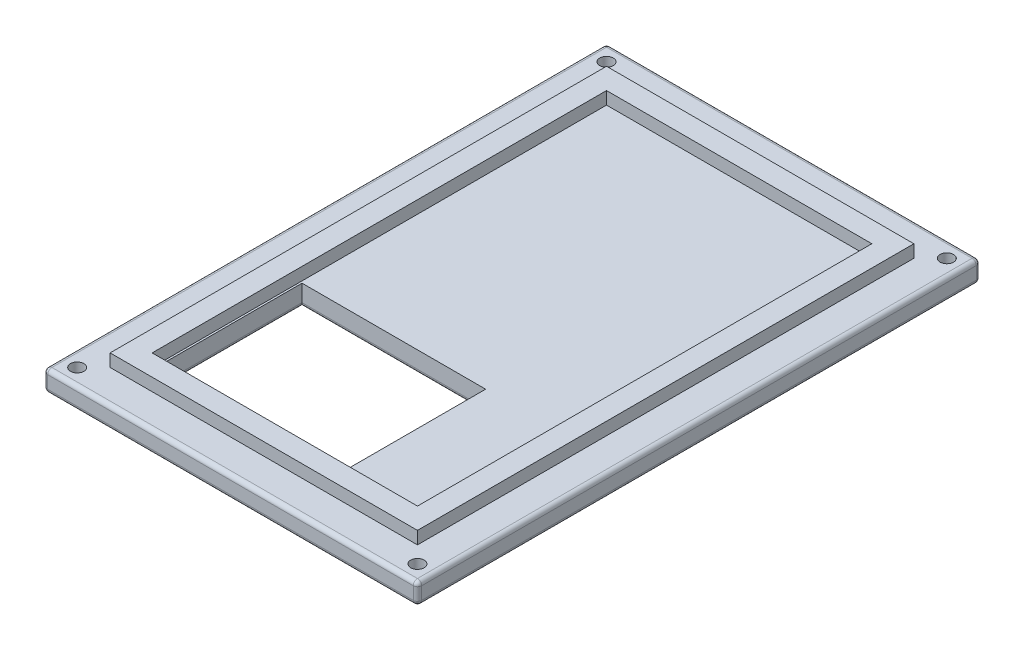
SolidWorks part; units mm, degrees
ref_plane "前基準面" through (0, 0, 0) normal (0, 0, 1) x (1, 0, 0)
ref_plane "上基準面" through (0, 0, 0) normal (0, 1, 0) x (1, 0, 0)
ref_plane "右基準面" through (0, 0, 0) normal (1, 0, 0) x (0, 0, -1)
sketch "Sketch1" plane through (0, 0, 0) normal (0, 1, 0) x (1, 0, 0)
  line L1 (-44.5, -67) -> (44.5, -67)
  line L2 (-44.5, -67) -> (-44.5, 67)
  line L3 (-44.5, 67) -> (44.5, 67)
  line L4 (44.5, -67) -> (44.5, 67)
  line L5 (-44.5, -67) -> (44.5, 67) construction
  line L6 (-44.5, 67) -> (44.5, -67) construction
  point P0 (0, 0)
  dimension "D1" = 89
  dimension "D2" = 134
extrude "Boss-Extrude1" add sketch "Sketch1" along normal mid plane 5
sketch "Sketch3" plane through (0, 2.5, 0) normal (0, 1, 0) x (1, 0, 0)
  line L0 (-31.575, -54.075) -> (-31.575, 54.075)
  line L1 (-36.575, -59.075) -> (36.575, -59.075)
  line L2 (-36.575, -59.075) -> (-36.575, 59.075)
  line L3 (-36.575, 59.075) -> (36.575, 59.075)
  line L4 (36.575, -59.075) -> (36.575, 59.075)
  line L5 (-36.575, -59.075) -> (36.575, 59.075) construction
  line L6 (-36.575, 59.075) -> (36.575, -59.075) construction
  line L7 (-31.575, 54.075) -> (31.575, 54.075)
  line L8 (31.575, -54.075) -> (31.575, 54.075)
  line L9 (-31.575, -54.075) -> (31.575, -54.075)
  point P0 (0, 0)
  dimension "D1" = 73.15
  dimension "D2" = 118.15
  dimension "D3" = 5
extrude "Boss-Extrude2" add sketch "Sketch3" along normal blind 3
sketch "Sketch5" plane through (0, -2.5, 0) normal (0, -1, 0) x (1, 0, 0)
  line L0 (-9.2606, 49.7699) -> (-9.2606, 23.1699) construction
  line L1 (3.7694, 49.7699) -> (-22.2906, 49.7699) construction
  line L2 (-0.5306, 23.1699) -> (-19.7906, 23.1699) construction
  line L3 (-9.2606, 23.1699) -> (-9.2606, 67) construction
  line L4 (44.5, 67) -> (-44.5, 67) construction
  line L5 (3.7694, 36.4199) -> (-24.1894, 36.4199) construction
  line L6 (3.7694, 49.7699) -> (3.7694, 23.0699) construction
  line L7 (44.5, -67) -> (-44.5, 67) construction
  line L8 (-31.575, 54.075) -> (31.575, 54.075) construction
  line L9 (12.5902, 18.8648) -> (-31.1113, 18.8648)
  line L10 (12.5902, 18.8648) -> (12.5902, 54.075)
  line L11 (12.5902, 54.075) -> (-31.1113, 54.075)
  line L12 (-31.1113, 18.8648) -> (-31.1113, 54.075)
  line L13 (12.5902, 18.8648) -> (-31.1113, 54.075) construction
  line L14 (12.5902, 54.075) -> (-31.1113, 18.8648) construction
  line L15 (-44.5, -67) -> (-44.5, 67) construction
  point P15 (-9.2606, 36.4699)
  dimension "D1" = 13.3887
extrude "Cut-Extrude1" cut sketch "Sketch5" against normal up to next
fillet "Fillet1" radius 1 16 edges at (44.5, 2.5, 0) (0, 2.5, 67) (44.5, 0, 67) (-44.5, 2.5, 0) (-44.5, 0, 67) (44.5, 0, -67) (0, 2.5, -67) (-44.5, 0, -67) (0, -2.5, -67) (-44.5, -2.5, 0) (0, -2.5, 67) (44.5, -2.5, 0) (-9.2606, -2.5, 18.8648) (12.5902, -2.5, 36.4699) (-9.2606, -2.5, 54.075) (-31.1113, -2.5, 36.4699)
sketch "Sketch8" plane through (0, -2.5, 0) normal (0, -1, 0) x (1, 0, 0)
  line L0 (43.5, -66) -> (35.4563, -57.9563) construction
  line L1 (44.5, 0) -> (-44.5, 0) construction
  line L2 (44.5, -67) -> (44.5, 67) construction
  line L3 (-44.5, -67) -> (-44.5, 67) construction
  line L4 (0, -67) -> (0, 67) construction
  line L5 (44.5, -67) -> (-44.5, -67) construction
  line L6 (44.5, 67) -> (-44.5, 67) construction
  circle A1 centre (40.4948, -62.9948) radius 2.9
  circle A2 centre (-40.4948, -62.9948) radius 2.9
  circle A3 centre (40.4948, 62.9948) radius 2.9
  circle A4 centre (-40.4948, 62.9948) radius 2.9
  dimension "D2" = 5.8
  dimension "D1" = 4.25
  dimension "D3" = 9.0437
  dimension "D4" = 9.0437
extrude "Cut-Extrude2" cut sketch "Sketch8" against normal blind 2.5
sketch "Sketch9" plane through (0, 0, 0) normal (0, -1, 0) x (1, 0, 0)
  circle A0 centre (40.4948, -62.9948) radius 1.6
  circle A1 centre (-40.4948, -62.9948) radius 1.6
  circle A2 centre (40.4948, 62.9948) radius 1.6
  circle A3 centre (-40.4948, 62.9948) radius 1.6
  dimension "D1" = 3.2
  dimension "D2" = 3.2
  dimension "D3" = 3.2
  dimension "D4" = 3.2
extrude "Cut-Extrude3" cut sketch "Sketch9" against normal up to surface (35.5 mm away)
